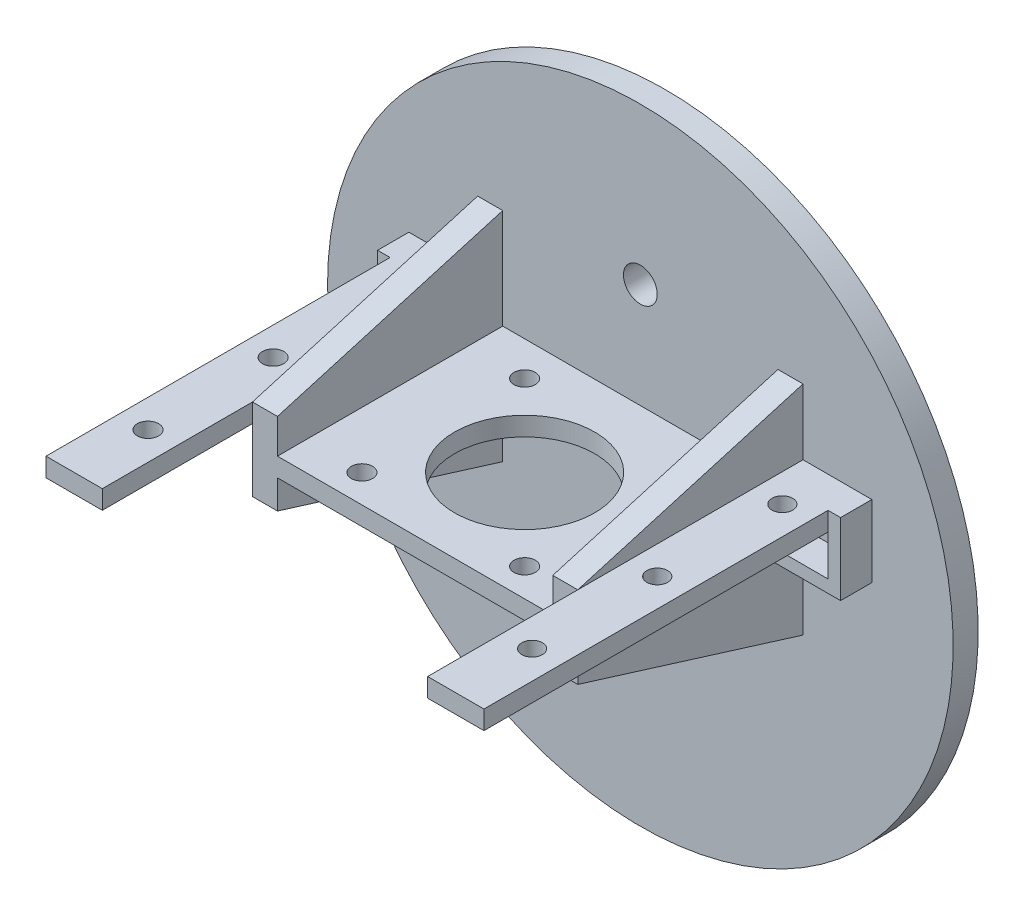
SolidWorks part; units mm, degrees
ref_plane "前视基准面" through (0, 0, 0) normal (0, 0, 1) x (1, 0, 0)
ref_plane "上视基准面" through (0, 0, 0) normal (0, 1, 0) x (1, 0, 0)
ref_plane "右视基准面" through (0, 0, 0) normal (1, 0, 0) x (0, 0, -1)
other "Configuration Table"
sketch "草图1" plane through (0, 0, 0) normal (0, 0, 1) x (1, 0, 0)
  line L1 (-35, -29) -> (35, -29)
  line L2 (-35, -29) -> (-35, 29)
  line L3 (-35, 29) -> (35, 29)
  line L4 (35, -29) -> (35, 29)
  line L5 (-35, -29) -> (35, 29) construction
  line L6 (-35, 29) -> (35, -29) construction
  point P0 (0, 0)
  dimension "D1" = 70
  dimension "D2" = 58
extrude "凸台-拉伸1" add sketch "草图1" along normal blind 4
sketch "草图2" plane through (0, 0, 4) normal (0, 0, 1) x (1, 0, 0)
  line L0 (-35, 29) -> (-35, -29) construction
  line L1 (-26, 15.5) -> (-35, 15.5)
  line L2 (-26, 15.5) -> (-26, 18.5)
  line L3 (-26, 18.5) -> (-35, 18.5)
  line L4 (-35, 15.5) -> (-35, 18.5)
  line L5 (35, -29) -> (35, 29) construction
  line L6 (26, 15.5) -> (35, 15.5)
  line L7 (26, 15.5) -> (26, 18.5)
  line L8 (26, 18.5) -> (35, 18.5)
  line L9 (35, 15.5) -> (35, 18.5)
  dimension "D1" = 3
  dimension "D2" = 3
extrude "凸台-拉伸2" add sketch "草图2" along normal blind 60
sketch "草图3" plane through (35, 0, 0) normal (1, 0, 0) x (0, 0, -1)
  line L0 (-4, 29) -> (-40, 18.5)
  line L1 (-64, 18.5) -> (-4, 18.5) construction
  line L3 (-40, 18.5) -> (-40, 15.5)
  line L4 (-40, 5.399) -> (-4, -5.7641)
  line L5 (-4, -29) -> (-4, 15.5) construction
  line L7 (0, -29) -> (0, 29) construction
  line L8 (0, -29) -> (0, 29)
  line L9 (0, 29) -> (-4, 29)
  line L10 (-4, -5.7641) -> (-4, -29)
  line L11 (-4, -29) -> (0, -29)
  line L13 (-64, 15.5) -> (-4, 15.5) construction
  line L14 (-40, 15.5) -> (-40, 5.399)
  dimension "D2" = 40
sketch "草图4" plane through (0, 29, 0) normal (0, 1, 0) x (1, 0, 0)
  line L4 (-35, 0) -> (-35, -4)
  line L5 (-35, 0) -> (-35, -4)
  line L6 (35, 0) -> (-35, 0)
  line L7 (35, -4) -> (35, 0)
  line L8 (35, -4) -> (35, 0)
  line L9 (-35, -4) -> (35, -4)
  line L12 (35, 0) -> (-35, 0)
  line L15 (-35, -4) -> (35, -4)
  dimension "D1" = 0
extrude "凸台-拉伸4" add sketch "草图4" along normal blind 9.5
extrude "凸台-拉伸5" add sketch "草图3" against normal blind 4 from offset 9 offset against normal yes
mirror "镜向2" about plane through (0, 0, 0) normal (1, 0, 0) of "凸台-拉伸5"
sketch "草图5" plane through (0, 0, 0) normal (0, 0, -1) x (-1, 0, 0)
  line L0 (43.5027, 4.75) -> (-51.1875, 4.75) construction
  line L1 (0, 43.8362) -> (0, -41.5793) construction
  circle A1 centre (0, 4.75) radius 50
  dimension "D1" = 100
extrude "凸台-拉伸6" add sketch "草图5" against normal blind 4
sketch "草图6" plane through (0, 0, 0) normal (0, 0, -1) x (-1, 0, 0)
  circle A0 centre (0, 4.75) radius 32.5
  dimension "D1" = 65
extrude "凸台-拉伸7" add sketch "草图6" along normal blind 6
sketch "草图7" plane through (0, 0, -6) normal (0, 0, -1) x (-1, 0, 0)
  circle A0 centre (0, 4.75) radius 20
  dimension "D1" = 40
extrude "切除-拉伸1" cut sketch "草图7" against normal blind 6
sketch "草图8" plane through (0, 0, -6) normal (0, 0, -1) x (-1, 0, 0)
  arc A0 (-24.8627, 2.1535) -> (24.8627, 2.1535) centre (0, 4.75) ccw construction
  circle A2 centre (0, -20.248) radius 2.7
  circle A4 centre (0, 29.748) radius 2.7
  arc A6 (24.8627, 7.3465) -> (-24.8627, 7.3465) centre (0, 4.75) ccw construction
  dimension "D1" = 49.9959
  dimension "D2" = 5.4
  dimension "D3" = 5.4
extrude "切除-拉伸2" cut sketch "草图8" against normal blind 10
sketch "草图9" plane through (0, 0, 0) normal (0, 0, -1) x (-1, 0, 0)
  circle A0 centre (-16, 4.75) radius 2.7
  circle A1 centre (16, 4.75) radius 2.7
  point P4 (0, 4.75)
  dimension "D1" = 5.4
  dimension "D2" = 5.4
  dimension "D3" = 16
  dimension "D4" = 16
extrude "切除-拉伸3" cut sketch "草图9" against normal blind 10
sketch "草图10" plane through (0, 0, 4) normal (0, 0, 1) x (1, 0, 0)
  line L0 (-17.5, 10) -> (17.5, 10)
ref_plane "基准面1" through (0, 10, 0) normal (0, 1, 0) x (1, 0, 0)
sketch "草图11" plane through (0, 10, 0) normal (0, 1, 0) x (1, 0, 0)
  line L0 (-17.5, -4) -> (17.5, -4) construction
  line L1 (-17.5, -4) -> (17.5, -4)
  line L3 (-17.5, -5) -> (17.5, -5) construction
  line L5 (0, -22.5) -> (-34.3239, 11.8239) construction
  line L6 (-17.5, -5) -> (17.5, -5) construction
  line L8 (-17.5, -40) -> (17.5, -40)
  line L11 (-17.5, -40) -> (-22, -40)
  line L13 (-17.5, -4) -> (-22, -4)
  line L14 (-22, -40) -> (-22, -4)
  line L15 (17.5, -40) -> (22, -40)
  line L17 (17.5, -4) -> (22, -4)
  line L18 (22, -40) -> (22, -4)
  circle A0 centre (0, -22.5) radius 11.2
  circle A1 centre (0, -22.5) radius 18.3848 construction
  circle A2 centre (-13, -9.5) radius 1.7
  circle A3 centre (13, -9.5) radius 1.7
  circle A4 centre (13, -35.5) radius 1.7
  circle A5 centre (-13, -35.5) radius 1.7
  point P16 (0, 0)
  dimension "D4" = 22.4
  dimension "D5" = 3.4
  dimension "D9" = 18.5
  dimension "D1" = 1
  dimension "D2" = 35
  dimension "D3" = 35
  dimension "D6" = 13
  dimension "D7" = 45
  dimension "D8" = 4
extrude "凸台-拉伸8" add sketch "草图11" along normal blind 3
sketch "草图13" plane through (0, 15.5, 0) normal (0, -1, 0) x (1, 0, 0)
  line L0 (30.5, 65.278) -> (30.5, -10.9518) construction
  line L1 (-35, 4) -> (-26, 4) construction
  line L2 (50, 4) -> (-50, 4) construction
  line L3 (0, 85.0436) -> (0, -31.3241) construction
  circle A0 centre (30.5, 11.8) radius 1.65
  circle A1 centre (30.5, 31.8) radius 1.65
  circle A2 centre (30.5, 51.8) radius 1.65
  circle A6 centre (-30.5, 12.2) radius 1.7
  circle A7 centre (-30.5, 32.2) radius 1.7
  circle A8 centre (-30.5, 52.2) radius 1.7
  dimension "D1" = 3.3
  dimension "D2" = 3.3
  dimension "D3" = 3.3
  dimension "D4" = 7.8
  dimension "D5" = 20
  dimension "D6" = 20
  dimension "D7" = 3.4
  dimension "D8" = 3.4
  dimension "D9" = 3.4
  dimension "D10" = 8.2
  dimension "D11" = 20
  dimension "D12" = 20
extrude "切除-拉伸4" cut sketch "草图13" against normal blind 10
sketch "草图14" plane through (0, 0, 4) normal (0, 0, 1) x (1, 0, 0)
  line L3 (26, 9) -> (35, 9)
  line L4 (35, 15.5) -> (35, 9)
  line L6 (26, 7) -> (37, 7)
  line L7 (37, 7) -> (37, 18.5)
  line L8 (37, 18.5) -> (35, 18.5)
  line L9 (35, 18.5) -> (35, 15.5)
  line L10 (26, 9) -> (26, 7)
  line L11 (26, 15.5) -> (26, 5.399) construction
  dimension "D1" = 6.5
  dimension "D2" = 2
  dimension "D3" = 2
extrude "凸台-拉伸9" add sketch "草图14" along normal blind 5
mirror "镜向3" about plane through (0, 0, 0) normal (1, 0, 0) of "凸台-拉伸9"
